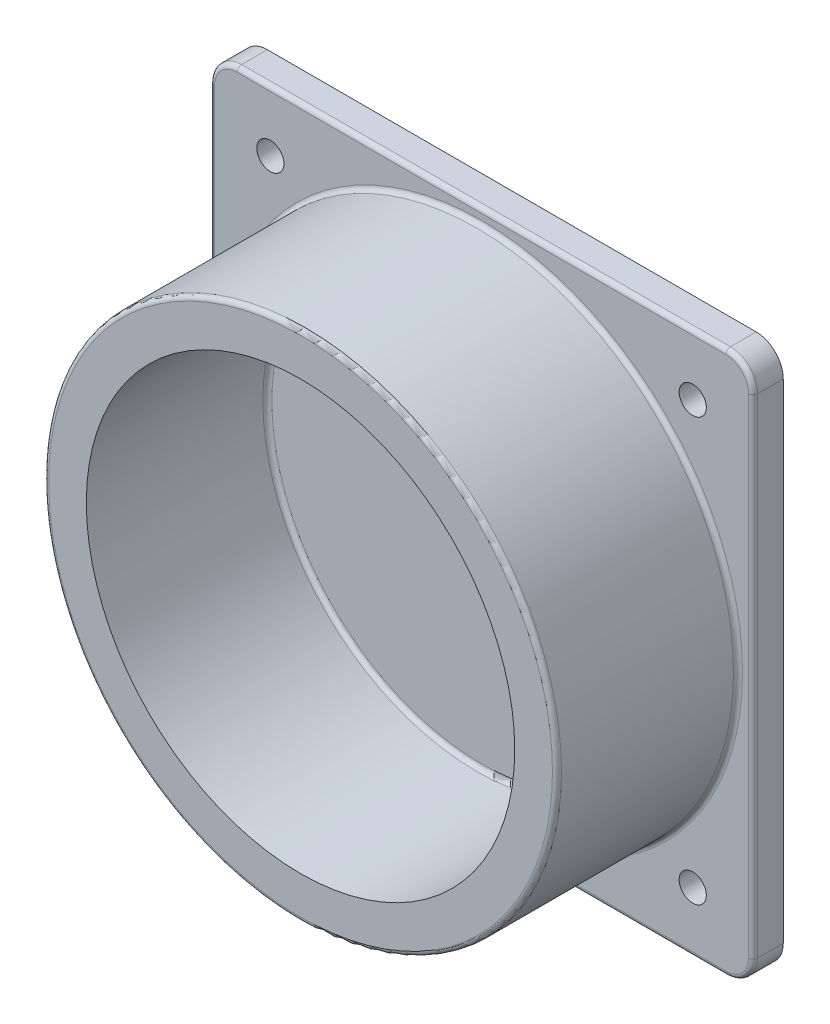
SolidWorks part; units mm, degrees
material "6061 Alloy"
ref_plane "Front Plane" through (0, 0, 0) normal (0, 0, 1) x (1, 0, 0)
ref_plane "Top Plane" through (0, 0, 0) normal (0, 1, 0) x (1, 0, 0)
ref_plane "Right Plane" through (0, 0, 0) normal (1, 0, 0) x (0, 0, -1)
sketch "Sketch1" plane through (0, 0, 0) normal (0, 0, 1) x (1, 0, 0)
  line L0 (0, 90) -> (0, 0) construction
  line L1 (-81, -90) -> (81, -90)
  line L2 (-90, -81) -> (-90, 81)
  line L3 (-81, 90) -> (81, 90)
  line L4 (90, -81) -> (90, 81)
  line L5 (-90, -90) -> (90, 90) construction
  line L6 (-90, 90) -> (90, -90) construction
  line L7 (0, 0) -> (90, 0) construction
  arc A0 (81, -90) -> (90, -81) centre (81, -81) ccw
  arc A1 (-81, -90) -> (-90, -81) centre (-81, -81) cw
  arc A2 (81, 90) -> (90, 81) centre (81, 81) cw
  arc A3 (-90, 81) -> (-81, 90) centre (-81, 81) cw
  circle A4 centre (0, 0) radius 9
  circle A5 centre (70, 70) radius 4.5
  circle A6 centre (-70, 70) radius 4.5
  circle A7 centre (70, -70) radius 4.5
  circle A8 centre (-70, -70) radius 4.5
  point P0 (0, 0)
  dimension "D2" = 9
  dimension "D3" = 18
  dimension "D4" = 9
  dimension "D1" = 180
  dimension "D5" = 70
extrude "Boss-Extrude1" add sketch "Sketch1" along normal blind 10
sketch "Sketch2" plane through (0, 0, 10) normal (0, 0, 1) x (1, 0, 0)
  circle A0 centre (0, 0) radius 85
  dimension "D1" = 170
extrude "Boss-Extrude2" add sketch "Sketch2" along normal blind 60
sketch "Sketch3" plane through (0, 0, 70) normal (0, 0, 1) x (1, 0, 0)
  circle A0 centre (0, 0) radius 71
  dimension "D1" = 142
extrude "Cut-Extrude1" cut sketch "Sketch3" against normal blind 60
fillet "Fillet1" radius 1.5 11 edges at (87.364, -87.364, 10) (0, -90, 10) (-87.364, -87.364, 10) (-90, 0, 10) (-87.364, 87.364, 10) (0, 90, 10) (87.364, 87.364, 10) (90, 0, 10) (85, 0, 10) (85, 0, 70) (71, 0, 10)
